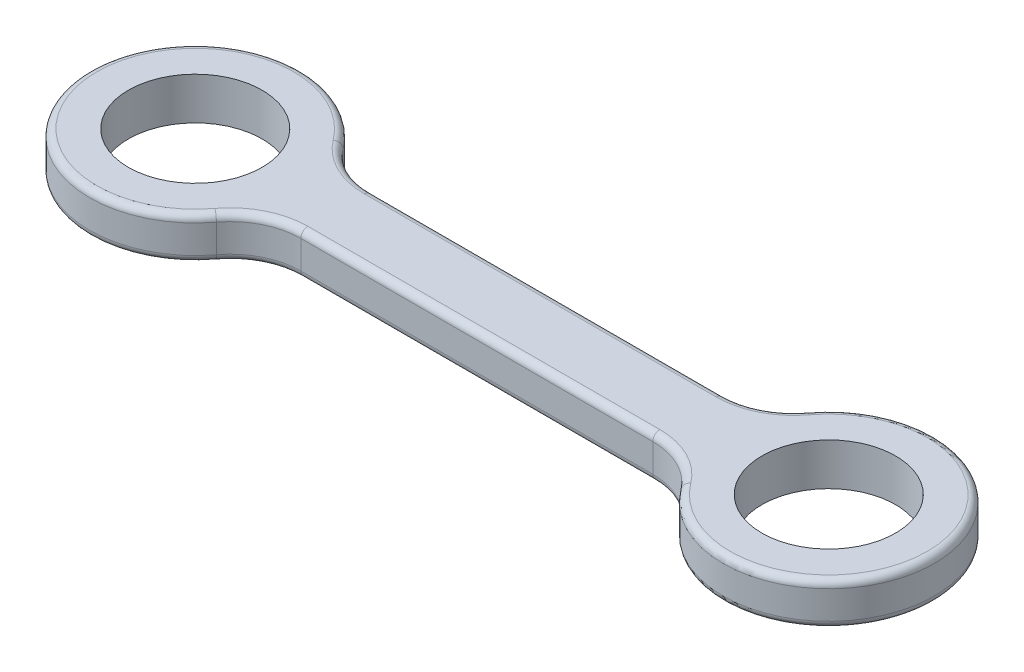
SolidWorks part; units mm, degrees
ref_plane "Front Plane" through (0, 0, 0) normal (0, 0, 1) x (1, 0, 0)
ref_plane "Top Plane" through (0, 0, 0) normal (0, 1, 0) x (1, 0, 0)
ref_plane "Right Plane" through (0, 0, 0) normal (1, 0, 0) x (0, 0, -1)
sketch "Sketch1" plane through (0, 0, 0) normal (0, 1, 0) x (1, 0, 0)
  line L1 (-28.046, 5) -> (21.954, 5)
  line L3 (-28.046, -5) -> (21.954, -5)
  circle A0 centre (-48.046, 0) radius 9.5
  circle A1 centre (41.954, 0) radius 9.5
  arc A2 (-36.046, 9) -> (-36.046, -9) centre (-48.046, 0) ccw
  arc A3 (29.954, -9) -> (29.954, 9) centre (41.954, 0) ccw
  arc A4 (29.954, 9) -> (21.954, 5) centre (21.954, 15) cw
  arc A5 (29.954, -9) -> (21.954, -5) centre (21.954, -15) ccw
  arc A6 (-28.046, -5) -> (-36.046, -9) centre (-28.046, -15) ccw
  arc A7 (-28.046, 5) -> (-36.046, 9) centre (-28.046, 15) cw
  point P6 (-48.046, 5)
  point P8 (31.954, 5)
  point P9 (-48.046, -5)
  point P10 (49.3563, -5)
  dimension "D1" = 19
  dimension "D2" = 19
  dimension "D3" = 30
  dimension "D4" = 30
  dimension "D5" = 10
  dimension "D6" = 90
  dimension "D7" = 10
extrude "Boss-Extrude1" add sketch "Sketch1" along normal blind 6
fillet "Fillet1" radius 1 16 edges at (-63.046, 0, 0) (-32.5181, 0, -6.0557) (-3.046, 0, -5) (26.4262, 0, -6.0557) (56.954, 0, 0) (26.4262, 0, 6.0557) (-3.046, 0, 5) (-32.5181, 6, 6.0557) (-63.046, 6, 0) (-32.5181, 6, -6.0557) (-3.046, 6, -5) (26.4262, 6, -6.0557) (56.954, 6, 0) (26.4262, 6, 6.0557) (-32.5181, 0, 6.0557) (-3.046, 6, 5)
